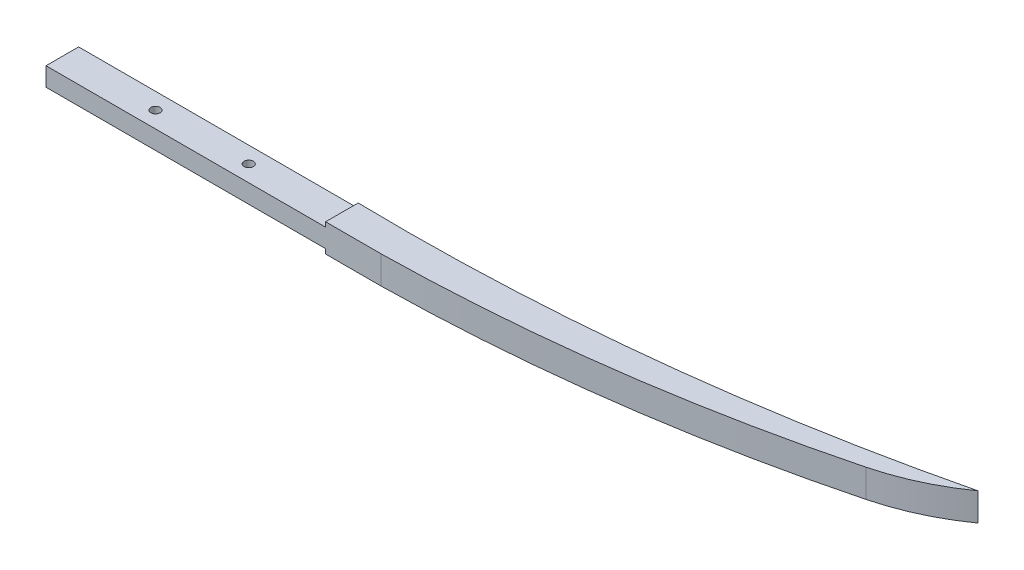
SolidWorks part; units mm, degrees
ref_plane "Front Plane" through (0, 0, 0) normal (0, 0, 1) x (1, 0, 0)
ref_plane "Top Plane" through (0, 0, 0) normal (0, 1, 0) x (1, 0, 0)
ref_plane "Right Plane" through (0, 0, 0) normal (1, 0, 0) x (0, 0, -1)
sketch "Sketch1" plane through (0, 0, 0) normal (0, 1, 0) x (1, 0, 0)
  line L0 (0, 0) -> (600, 0)
  line L1 (600, 0) -> (600, 100)
  line L2 (600, 100) -> (0, 100)
  line L3 (0, 100) -> (0, 0)
  arc A0 (0, 35) -> (600, 100) centre (48.9928, 2384.4892) ccw
  arc A1 (0, 0) -> (517.9794, 61.8895) centre (29.7233, 1949.7735) ccw
  arc A2 (517.9794, 61.8895) -> (600, 100) centre (455.3824, 303.9259) ccw
  dimension "D4" = 2350
  dimension "D5" = 1950
  dimension "D6" = 250
  dimension "D1" = 600
  dimension "D2" = 100
  dimension "D3" = 35
  dimension "D7" = 38.1105
extrude "Boss-Extrude1" add sketch "Sketch1" along normal blind 30 contours A1 A2 A0 L3 L0
sketch "Sketch2" plane through (0, 0, 0) normal (-1, 0, 0) x (0, 0, 1)
  line L0 (0, 25) -> (-35, 25)
  line L1 (0, 30) -> (0, 0) construction
  line L2 (-35, 30) -> (-35, 0) construction
  line L3 (-35, 5) -> (0, 5)
  line L4 (0, 5) -> (0, 25)
  line L5 (-35, 5) -> (-35, 25)
  line L6 (-35, 0) -> (0, 0) construction
  line L7 (-35, 30) -> (0, 30) construction
  dimension "D1" = 5
  dimension "D2" = 5
extrude "Boss-Extrude2" add sketch "Sketch2" along normal blind 300
hole_wizard "Ø10.0mm Dowel Hole1" positions "Sketch3" profile "Sketch4" hole size "Ø10.0" standard "ANSI Metric" end condition through all
sketch "Sketch3" plane through (0, 25, 0) normal (0, 1, 0) x (1, 0, 0)
  point P0 (-200, 17.5)
  point P2 (-100, 17.5)
  dimension "D1" = 100
  dimension "D2" = 200
  dimension "D3" = 17.5
  dimension "D4" = 17.5
sketch "Sketch4" plane through (-200, 25, -17.5) normal (1, 0, 0) x (0, 0, 1)
  line L0 (0, 0) -> (0, 25)
  line L1 (0, 25) -> (5, 25)
  line L2 (5, 25) -> (5, 0)
  line L5 (5, 0) -> (0, 0)
  line L11 (0, -6.35) -> (0, 107.95) construction
  dimension "Thru Hole Dia." = 10
  dimension "Thru Hole Depth" = 25
